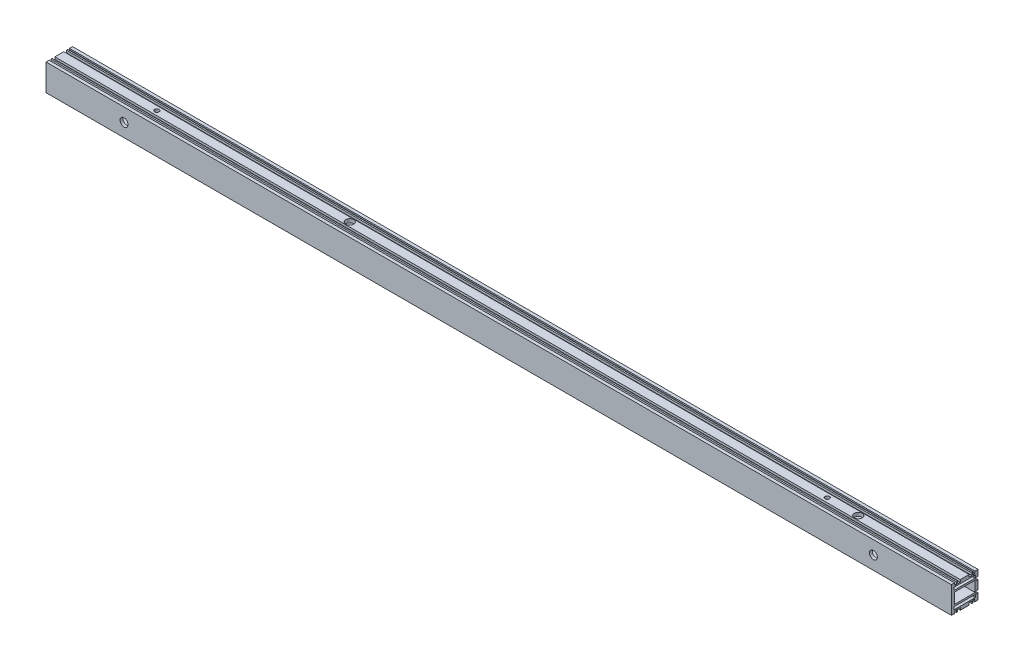
SolidWorks part; units mm, degrees
ref_plane "前视基准面" through (0, 0, 0) normal (0, 0, 1) x (1, 0, 0)
ref_plane "上视基准面" through (0, 0, 0) normal (0, 1, 0) x (1, 0, 0)
ref_plane "右视基准面" through (0, 0, 0) normal (1, 0, 0) x (0, 0, -1)
sketch "草图1" plane through (0, 0, 0) normal (1, 0, 0) x (0, 0, -1)
  line L0 (-15, 15) -> (15, -15) construction
  line L1 (-15, 15) -> (-11.5, 15)
  line L2 (-15, 15) -> (-15, -15)
  line L3 (-15, -15) -> (-11.5, -15)
  line L4 (15, 15) -> (15, 8)
  line L5 (15, 15) -> (-15, -15) construction
  line L6 (-11.5, 15) -> (-11.5, 13.5)
  line L7 (-11.5, 13.5) -> (-11, 13.5)
  line L8 (-11, 13.5) -> (-11, 12)
  line L9 (-11, 12) -> (-9.5, 12)
  line L10 (-9.5, 12) -> (-9.5, 15)
  line L11 (-9.5, 15) -> (-8, 15)
  line L12 (-8, 15) -> (-8, 12.5)
  line L13 (-8, 12.5) -> (-5, 12.5)
  line L14 (-5, 12.5) -> (-5, 15)
  line L15 (-5, 15) -> (5, 15)
  line L16 (0, 21.5201) -> (0, -18.309) construction
  line L17 (0, 55) -> (0, -55) construction
  line L18 (5, 12.5) -> (5, 15)
  line L19 (8, 12.5) -> (5, 12.5)
  line L20 (8, 15) -> (8, 12.5)
  line L21 (9.5, 15) -> (8, 15)
  line L22 (9.5, 12) -> (9.5, 15)
  line L23 (11, 12) -> (9.5, 12)
  line L24 (11, 13.5) -> (11, 12)
  line L25 (11.5, 13.5) -> (11, 13.5)
  line L26 (11.5, 15) -> (11.5, 13.5)
  line L27 (8, 15) -> (9.5, 15)
  line L28 (11.5, 15) -> (15, 15)
  line L29 (-19.8303, 0) -> (22.13, 0) construction
  line L30 (55, 0) -> (-55, 0) construction
  line L31 (8, -15) -> (9.5, -15)
  line L32 (11.5, -15) -> (11.5, -13.5)
  line L33 (11.5, -13.5) -> (11, -13.5)
  line L34 (11, -13.5) -> (11, -12)
  line L35 (11, -12) -> (9.5, -12)
  line L36 (9.5, -12) -> (9.5, -15)
  line L37 (9.5, -15) -> (8, -15)
  line L38 (8, -15) -> (8, -12.5)
  line L39 (8, -12.5) -> (5, -12.5)
  line L40 (5, -12.5) -> (5, -15)
  line L41 (-5, -15) -> (5, -15)
  line L42 (-5, -12.5) -> (-5, -15)
  line L43 (-8, -12.5) -> (-5, -12.5)
  line L44 (-8, -15) -> (-8, -12.5)
  line L45 (-9.5, -15) -> (-8, -15)
  line L46 (-9.5, -12) -> (-9.5, -15)
  line L47 (-11, -12) -> (-9.5, -12)
  line L48 (-11, -13.5) -> (-11, -12)
  line L49 (-11.5, -13.5) -> (-11, -13.5)
  line L50 (-11.5, -15) -> (-11.5, -13.5)
  line L51 (-9.5, -15) -> (-8, -15)
  line L52 (-5, -15) -> (5, -15)
  line L53 (8, -15) -> (9.5, -15)
  line L54 (11.5, -15) -> (15, -15)
  line L55 (15, 8) -> (12.5, 8)
  line L56 (12.5, 8) -> (12.5, 5)
  line L57 (12.5, 5) -> (15, 5)
  line L58 (12.5, -5) -> (15, -5)
  line L59 (12.5, -8) -> (12.5, -5)
  line L60 (15, -8) -> (12.5, -8)
  line L61 (15, 5) -> (15, -5)
  line L62 (15, -8) -> (15, -15)
  line L63 (12, -10.5) -> (12, -8.5)
  line L64 (-11.5, 11) -> (11.5, 11)
  line L65 (-12, 10.5) -> (-12, 8.5)
  line L66 (-11.5, 8) -> (11.5, 8)
  line L67 (12, 10.5) -> (12, 8.5)
  line L68 (-11.5, -8) -> (11.5, -8)
  line L69 (-12, -10.5) -> (-12, -8.5)
  line L70 (-11.5, -11) -> (11.5, -11)
  line L72 (-11.75, 6) -> (11.75, 6)
  line L73 (-11.75, 6) -> (-11.75, -6)
  line L74 (-11.75, -6) -> (11.75, -6)
  line L75 (11.75, 6) -> (11.75, -6)
  arc A0 (12, 8.5) -> (11.5, 8) centre (11.5, 8.5) cw
  arc A1 (11.5, 11) -> (12, 10.5) centre (11.5, 10.5) cw
  arc A2 (-11.5, 11) -> (-12, 10.5) centre (-11.5, 10.5) ccw
  arc A3 (-11.5, 8) -> (-12, 8.5) centre (-11.5, 8.5) cw
  arc A8 (-11.5, -8) -> (-12, -8.5) centre (-11.5, -8.5) ccw
  arc A9 (-11.5, -11) -> (-12, -10.5) centre (-11.5, -10.5) cw
  arc A10 (11.5, -11) -> (12, -10.5) centre (11.5, -10.5) ccw
  arc A11 (12, -8.5) -> (11.5, -8) centre (11.5, -8.5) ccw
  point P69 (12, 11)
  point P72 (-12, 11)
  point P77 (-11, -13.5)
  point P80 (11, -13.5)
  point P83 (11, 13.5)
  point P86 (-11, 13.5)
  point P99 (-12, -11)
  point P100 (12, -11)
  dimension "D17" = 0.5
  dimension "D1" = 3.5
  dimension "D2" = 1.5
  dimension "D3" = 0.5
  dimension "D4" = 1.5
  dimension "D5" = 3
  dimension "D6" = 30
  dimension "D7" = 30
  dimension "D8" = 1.5
  dimension "D9" = 2.5
  dimension "D10" = 3
  dimension "D11" = 2.5
  dimension "D12" = 7
  dimension "D13" = 3
  dimension "D14" = 4
  dimension "D15" = 3
  dimension "D16" = 24
  dimension "D19" = 23.5
  dimension "D20" = 12
extrude "凸台-拉伸1" add sketch "草图1" along normal mid plane 1021
hole_wizard "M6 螺纹孔1" positions "草图3" profile "草图2" tap size "M6" standard "GB"
sketch "草图3" plane through (0, 0, -15) normal (0, 0, -1) x (-1, 0, 0)
  line L0 (-510.5, 15) -> (510.5, 15) construction
  line L1 (510.5, 5) -> (510.5, -5) construction
  point P0 (460.5, 0)
  point P3 (-460.5, 0)
  point P6 (445.5, 0)
  point P9 (-445.5, 0)
  point P12 (368.5, 0)
  point P14 (317.5, 0)
  dimension "D1" = 15
  dimension "D2" = 15
  dimension "D3" = 51
  dimension "D4" = 142
sketch "草图2" plane through (-460.5, 0, -15) normal (1, 0, 0) x (0, 1, 0)
  line L0 (0, 0) -> (0, 16.5022)
  line L1 (0, 16.5022) -> (2.5, 15)
  line L2 (2.5, 15) -> (2.5, 0)
  line L5 (2.5, 0) -> (0, 0)
  line L10 (0, 16.5022) -> (-2.5, 15) construction
  line L11 (0, -6.35) -> (0, 107.95) construction
  dimension "螺纹孔钻头直径" = 5
  dimension "螺纹孔钻头深度" = 15
  dimension "导头角度" = 118
cosmetic thread "孔螺蚊线1" parameters "D1"=3.25, "D2"=6
cosmetic thread "孔螺蚊线2" parameters "D1"=3.25, "D2"=6
cosmetic thread "孔螺蚊线6" parameters "D1"=3.25, "D2"=6
cosmetic thread "孔螺蚊线7" parameters "D1"=3.25, "D2"=6
cosmetic thread "孔螺蚊线13" parameters "D1"=3.25, "D2"=6
cosmetic thread "孔螺蚊线14" parameters "D1"=3.25, "D2"=6
hole_wizard "M6 螺纹孔2" positions "草图5" profile "草图4" tap size "M6" standard "GB"
sketch "草图5" plane through (0, -15, 0) normal (0, -1, 0) x (-1, 0, 0)
  point P0 (-460.5, 0)
  point P3 (-230.5, 0)
  point P6 (460.5, 0)
  point P9 (-445.5, 0)
  point P12 (-215.5, 0)
  point P15 (445.5, 0)
sketch "草图4" plane through (460.5, -15, 0) normal (1, 0, 0) x (0, 0, -1)
  line L0 (0, 0) -> (0, 16.5022)
  line L1 (0, 16.5022) -> (2.5, 15)
  line L2 (2.5, 15) -> (2.5, 0)
  line L5 (2.5, 0) -> (0, 0)
  line L10 (0, 16.5022) -> (-2.5, 15) construction
  line L11 (0, -6.35) -> (0, 107.95) construction
  dimension "螺纹孔钻头直径" = 5
  dimension "螺纹孔钻头深度" = 15
  dimension "导头角度" = 118
cosmetic thread "孔螺蚊线3" parameters "D1"=9, "D2"=6
cosmetic thread "孔螺蚊线4" parameters "D1"=9, "D2"=6
cosmetic thread "孔螺蚊线5" parameters "D1"=9, "D2"=6
cosmetic thread "孔螺蚊线8" parameters "D1"=9, "D2"=6
cosmetic thread "孔螺蚊线9" parameters "D1"=9, "D2"=6
cosmetic thread "孔螺蚊线10" parameters "D1"=9, "D2"=6
hole_wizard "Ø9.0 (9) 直径孔1" positions "草图7" profile "草图8" hole size "Ø9.0" standard "GB" end condition through all
sketch "草图7" plane through (0, 0, 15) normal (0, 0, 1) x (1, 0, 0)
  line L0 (-510.5, 15) -> (-510.5, -15) construction
  line L1 (510.5, 15) -> (-510.5, 15) construction
  line L2 (510.5, 15) -> (510.5, -15) construction
  point P0 (-422.5, 0)
  point P2 (422.5, 0)
  dimension "D1" = 88
  dimension "D2" = 15
  dimension "D3" = 88
  dimension "D4" = 15
sketch "草图8" plane through (-422.5, 0, 15) normal (1, 0, 0) x (0, -1, 0)
  line L0 (0, 0) -> (0, 30)
  line L1 (0, 30) -> (4.5, 30)
  line L2 (4.5, 30) -> (4.5, 0)
  line L5 (4.5, 0) -> (0, 0)
  line L11 (0, -6.35) -> (0, 107.95) construction
  dimension "通孔孔直径" = 9
  dimension "通孔孔深度" = 30
hole_wizard "M6 螺纹孔3" positions "草图10" profile "草图9" tap size "M6" standard "GB"
sketch "草图10" plane through (0, 15, 0) normal (0, 1, 0) x (1, 0, 0)
  line L0 (510.5, 15) -> (-510.5, 15) construction
  line L1 (-510.5, -5) -> (-510.5, 5) construction
  line L2 (510.5, -5) -> (510.5, 5) construction
  point P0 (355.5, 0)
  point P2 (-400.5, 0)
  dimension "D1" = 15
  dimension "D2" = 110
  dimension "D3" = 155
  dimension "D4" = 15
sketch "草图9" plane through (355.5, 15, 0) normal (1, 0, 0) x (0, 0, 1)
  line L0 (0, 0) -> (0, 16.5022)
  line L1 (0, 16.5022) -> (2.5, 15)
  line L2 (2.5, 15) -> (2.5, 0)
  line L5 (2.5, 0) -> (0, 0)
  line L10 (0, 16.5022) -> (-2.5, 15) construction
  line L11 (0, -6.35) -> (0, 107.95) construction
  dimension "螺纹孔钻头直径" = 5
  dimension "螺纹孔钻头深度" = 15
  dimension "导头角度" = 118
cosmetic thread "孔螺蚊线11" parameters "D1"=9, "D2"=6
cosmetic thread "孔螺蚊线12" parameters "D1"=9, "D2"=6
hole_wizard "M6 螺纹孔的螺纹孔钻头2" positions "草图12" profile "草图11" hole size "M6" standard "GB"
sketch "草图12" plane through (0, -15, 0) normal (0, -1, 0) x (-1, 0, 0)
  line L0 (-510.5, 15) -> (510.5, 15) construction
  line L1 (-510.5, -5) -> (-510.5, 5) construction
  point P0 (-215.5, 0)
  point P2 (-230.5, 0)
  dimension "D1" = 15
  dimension "D2" = 15
  dimension "D3" = 280
  dimension "D4" = 295
sketch "草图11" plane through (215.5, -15, 0) normal (1, 0, 0) x (0, 0, -1)
  line L0 (0, 0) -> (0, 16.5022)
  line L1 (0, 16.5022) -> (2.5, 15)
  line L2 (2.5, 15) -> (2.5, 0)
  line L5 (2.5, 0) -> (0, 0)
  line L10 (0, 16.5022) -> (-2.5, 15) construction
  line L11 (0, -6.35) -> (0, 107.95) construction
  dimension "孔直径" = 5
  dimension "孔深度" = 15
  dimension "导头角度" = 118
hole_wizard "Ø7.0 (7) 直径孔1" positions "草图14" profile "草图13" hole size "Ø7.0" standard "GB"
sketch "草图14" plane through (0, -15, 0) normal (0, -1, 0) x (-1, 0, 0)
  line L0 (-510.5, 15) -> (510.5, 15) construction
  line L1 (510.5, -5) -> (510.5, 5) construction
  line L3 (-510.5, -5) -> (-510.5, 5) construction
  point P0 (-355.5, 0)
  point P2 (400.5, 0)
  dimension "D1" = 15
  dimension "D2" = 110
  dimension "D3" = 155
sketch "草图13" plane through (355.5, -15, 0) normal (1, 0, 0) x (0, 0, -1)
  line L0 (0, 0) -> (0, 17.103)
  line L1 (0, 17.103) -> (3.5, 15)
  line L2 (3.5, 15) -> (3.5, 0)
  line L5 (3.5, 0) -> (0, 0)
  line L10 (0, 17.103) -> (-3.5, 15) construction
  line L11 (0, -6.35) -> (0, 107.95) construction
  dimension "孔直径" = 7
  dimension "孔深度" = 15
  dimension "导头角度" = 118
hole_wizard "Ø9.0 (9) 直径孔2" positions "草图19" profile "草图18" hole size "Ø9.0" standard "GB" end condition through all
sketch "草图19" plane through (0, -15, 0) normal (0, -1, 0) x (-1, 0, 0)
  line L0 (-510.5, 15) -> (510.5, 15) construction
  line L1 (510.5, -5) -> (510.5, 5) construction
  line L2 (-510.5, -5) -> (-510.5, 5) construction
  point P0 (-390.5, 0)
  point P2 (183, 0)
  dimension "D1" = 15
  dimension "D2" = 327.5
  dimension "D3" = 15
  dimension "D4" = 120
sketch "草图18" plane through (390.5, -15, 0) normal (1, 0, 0) x (0, 0, -1)
  line L0 (0, 0) -> (0, 30)
  line L1 (0, 30) -> (4.5, 30)
  line L2 (4.5, 30) -> (4.5, 0)
  line L5 (4.5, 0) -> (0, 0)
  line L11 (0, -6.35) -> (0, 107.95) construction
  dimension "通孔孔直径" = 9
  dimension "通孔孔深度" = 30
